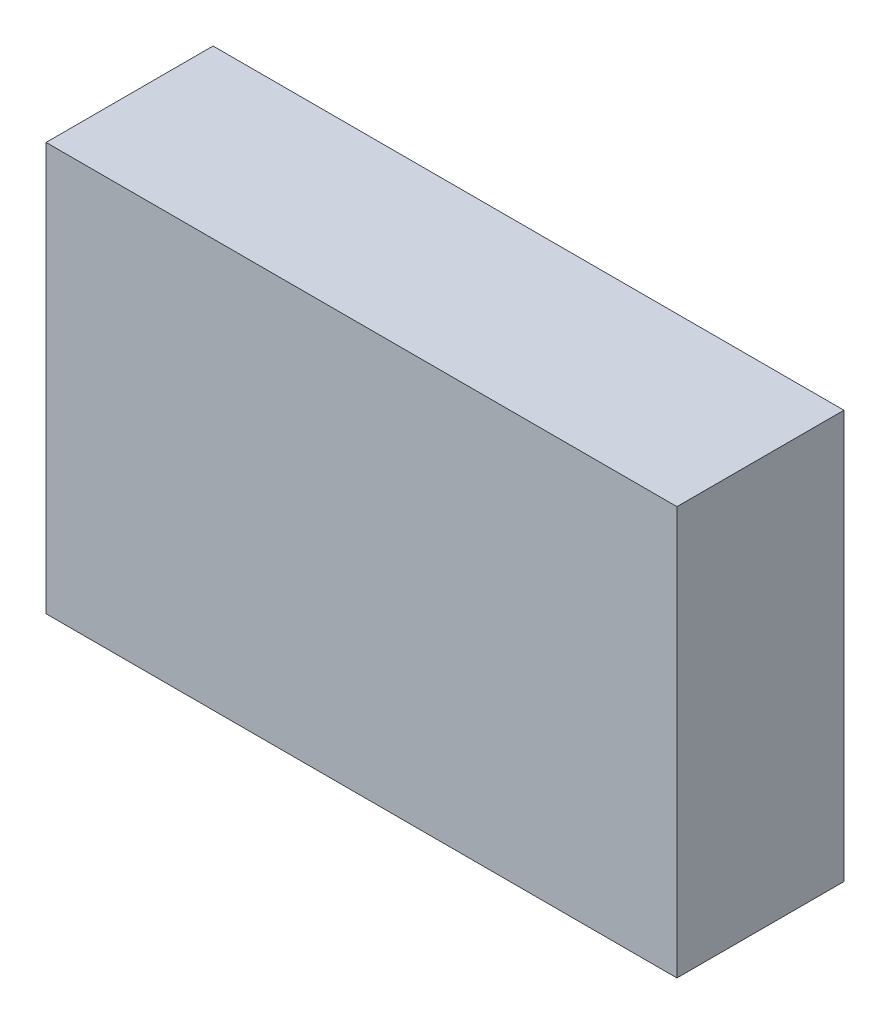
SolidWorks part; units mm, degrees
material "Custom Plastic"
ref_plane "X-Y Datum" through (0, 0, 0) normal (0, 0, 1) x (1, 0, 0)
ref_plane "X-Z Datum" through (0, 0, 0) normal (0, 1, 0) x (1, 0, 0)
ref_plane "Y-Z Datum" through (0, 0, 0) normal (1, 0, 0) x (0, 0, -1)
sketch "Sketch1" plane through (0, 0, 0) normal (0, 0, 1) x (1, 0, 0)
  line L1 (-107.95, -69.85) -> (107.95, -69.85)
  line L2 (-107.95, -69.85) -> (-107.95, 69.85)
  line L3 (-107.95, 69.85) -> (107.95, 69.85)
  line L4 (107.95, -69.85) -> (107.95, 69.85)
  line L5 (-107.95, -69.85) -> (107.95, 69.85) construction
  line L6 (-107.95, 69.85) -> (107.95, -69.85) construction
  point P0 (0, 0)
  dimension "D1" = 215.9
  dimension "D2" = 139.7
extrude "Boss-Extrude1" add sketch "Sketch1" along normal blind 57.15
